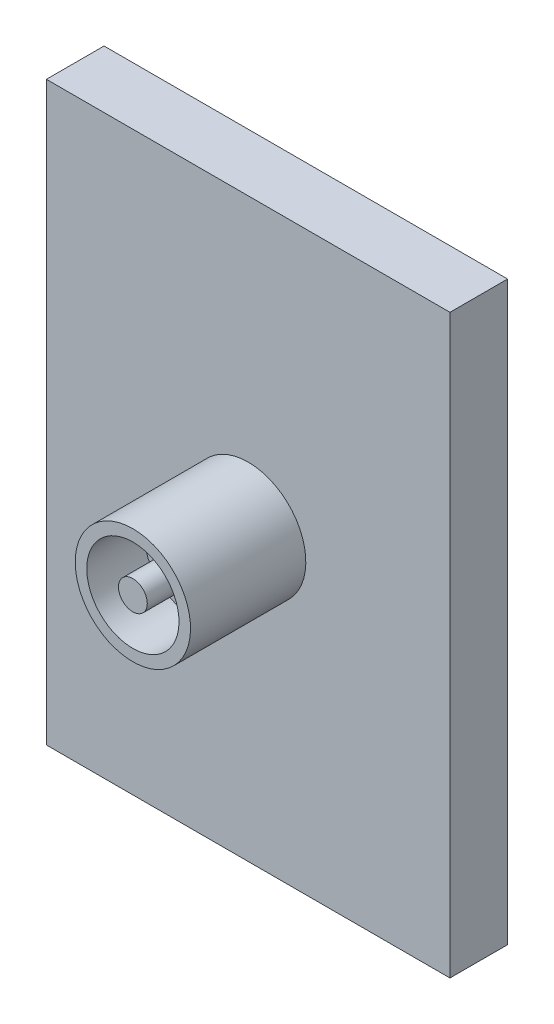
SolidWorks part; units mm, degrees
ref_plane "Front Plane" through (0, 0, 0) normal (0, 0, 1) x (1, 0, 0)
ref_plane "Top Plane" through (0, 0, 0) normal (0, 1, 0) x (1, 0, 0)
ref_plane "Right Plane" through (0, 0, 0) normal (1, 0, 0) x (0, 0, -1)
sketch "Sketch1" plane through (0, 0, 0) normal (0, 0, 1) x (1, 0, 0)
  line L1 (-35, -50) -> (35, -50)
  line L2 (-35, -50) -> (-35, 50)
  line L3 (-35, 50) -> (35, 50)
  line L4 (35, -50) -> (35, 50)
  line L5 (-35, -50) -> (35, 50) construction
  line L6 (-35, 50) -> (35, -50) construction
  point P0 (0, 0)
  dimension "D1" = 100
  dimension "D2" = 70
extrude "Boss-Extrude1" add sketch "Sketch1" along normal mid plane 10
sketch "Sketch2" plane through (0, 0, 5) normal (0, 0, 1) x (1, 0, 0)
  line L0 (16.5, 0) -> (-16.5, 0) construction
  circle A0 centre (0, 30) radius 4
  dimension "D1" = 30
  dimension "D2" = 8
sketch "Sketch3" plane through (0, 0, 5) normal (0, 0, 1) x (1, 0, 0)
  circle A0 centre (0, 0) radius 2.5
  dimension "D1" = 5
extrude "Boss-Extrude2" add sketch "Sketch3" along normal blind 20
sketch "Sketch5" plane through (0, 0, 0) normal (1, 0, 0) x (0, 0, -1)
  line L0 (-5, -50) -> (-5, 50) construction
  line L1 (-5, -50) -> (-5, 50) construction
  line L2 (-5, 6) -> (-15, 6)
  line L3 (-15, 6) -> (-15, 8)
  line L4 (-15, 8) -> (-25, 8)
  line L5 (-25, 8) -> (-25, 10)
  line L6 (-25, 10) -> (-5, 10)
  line L7 (-5, 10) -> (-5, 6)
  line L9 (0, 0) -> (-31.5999, 0) construction
  dimension "D1" = 12
  dimension "D2" = 2
  dimension "D3" = 2
  dimension "D4" = 10
  dimension "D5" = 10
revolve "Revolve1" add sketch "Sketch5" angle 360 about L9
